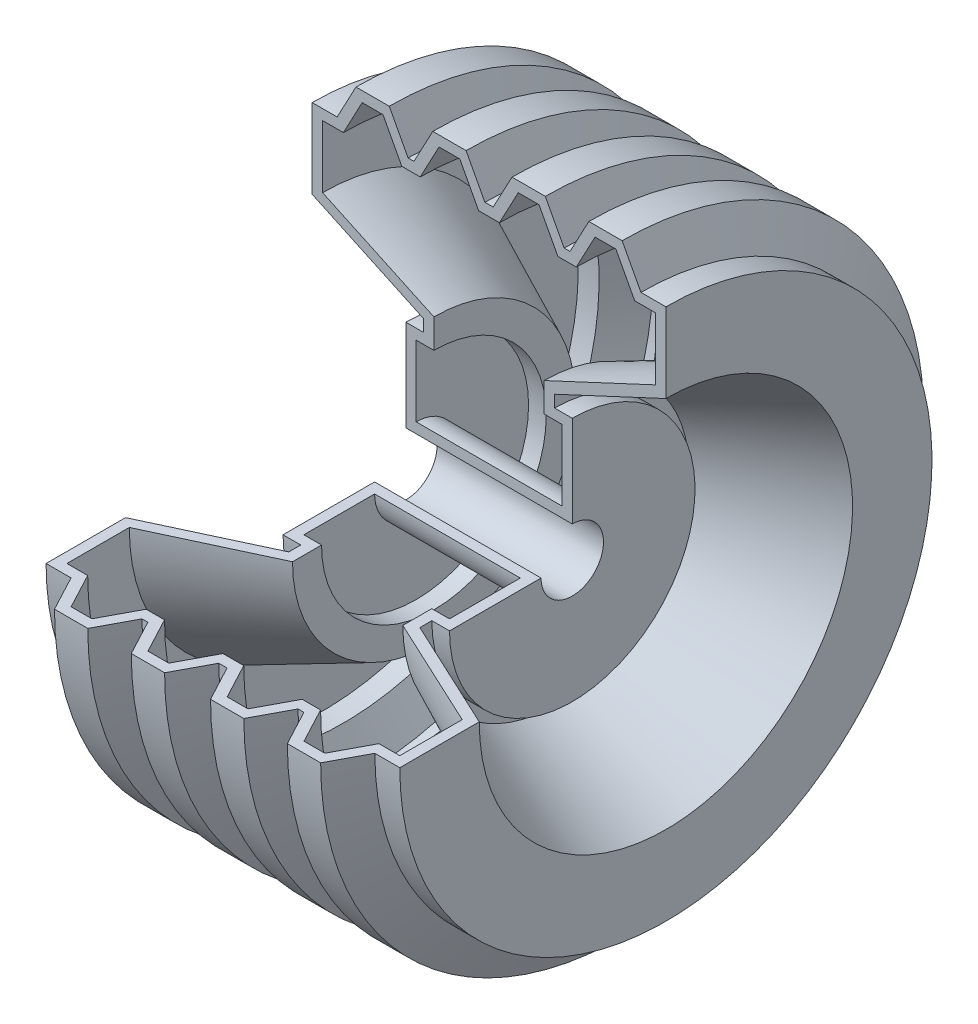
SolidWorks part; units mm, degrees
ref_plane "Front Plane" through (0, 0, 0) normal (0, 0, 1) x (1, 0, 0)
ref_plane "Top Plane" through (0, 0, 0) normal (0, 1, 0) x (1, 0, 0)
ref_plane "Right Plane" through (0, 0, 0) normal (1, 0, 0) x (0, 0, -1)
sketch "Sketch1" plane through (0, 0, 0) normal (0, 0, 1) x (1, 0, 0)
  line L0 (0, 0) -> (0, -47837.6075) construction
  line L1 (0, 0) -> (-47837.6075, 0) construction
  line L2 (-35, 20) -> (35, 20)
  line L3 (35, 20) -> (35, 54)
  line L4 (35, 54) -> (26.5, 54)
  line L5 (26.5, 54) -> (26.5, 67.9477)
  line L6 (26.5, 67.9477) -> (80, 92.8952)
  line L7 (80, 92.8952) -> (80, 122.8952)
  line L8 (80, 122.8952) -> (70, 122.8952)
  line L9 (70, 122.8952) -> (60.9609, 139.8952)
  line L23 (-80, 92.8952) -> (-80, 122.8952)
  line L24 (-26.5, 67.9477) -> (-80, 92.8952)
  line L25 (-26.5, 54) -> (-26.5, 67.9477)
  line L26 (-35, 54) -> (-26.5, 54)
  line L27 (-35, 20) -> (-35, 54)
  line L33 (14.0391, 139.8952) -> (5, 122.8952)
  line L34 (24.0391, 139.8952) -> (14.0391, 139.8952)
  line L35 (33.0781, 122.8952) -> (24.0391, 139.8952)
  line L36 (41.9219, 122.8952) -> (33.0781, 122.8952)
  line L37 (50.9609, 139.8952) -> (41.9219, 122.8952)
  line L38 (50.9609, 139.8952) -> (60.9609, 139.8952)
  line L39 (-50.9609, 139.8952) -> (-60.9609, 139.8952)
  line L40 (-50.9609, 139.8952) -> (-41.9219, 122.8952)
  line L41 (-41.9219, 122.8952) -> (-33.0781, 122.8952)
  line L42 (-33.0781, 122.8952) -> (-24.0391, 139.8952)
  line L43 (-24.0391, 139.8952) -> (-14.0391, 139.8952)
  line L44 (-14.0391, 139.8952) -> (-5, 122.8952)
  line L45 (-70, 122.8952) -> (-60.9609, 139.8952)
  line L46 (-80, 122.8952) -> (-70, 122.8952)
  line L47 (-5, 122.8952) -> (5, 122.8952)
  point P8 (0, 20)
  point P22 (0, 122.8952)
  dimension "D1" = 70
  dimension "D2" = 40
  dimension "D3" = 108
  dimension "D4" = 53
  dimension "D5" = 10
  dimension "D6" = 65
  dimension "D7" = 30
  dimension "D8" = 160
  dimension "D9" = 17
  dimension "D10" = 10
  dimension "D11" = 10
  dimension "D12" = 62
  dimension "D14" = 62
revolve "Revolve-Thin1" add sketch "Sketch1" angle 270 about L1
